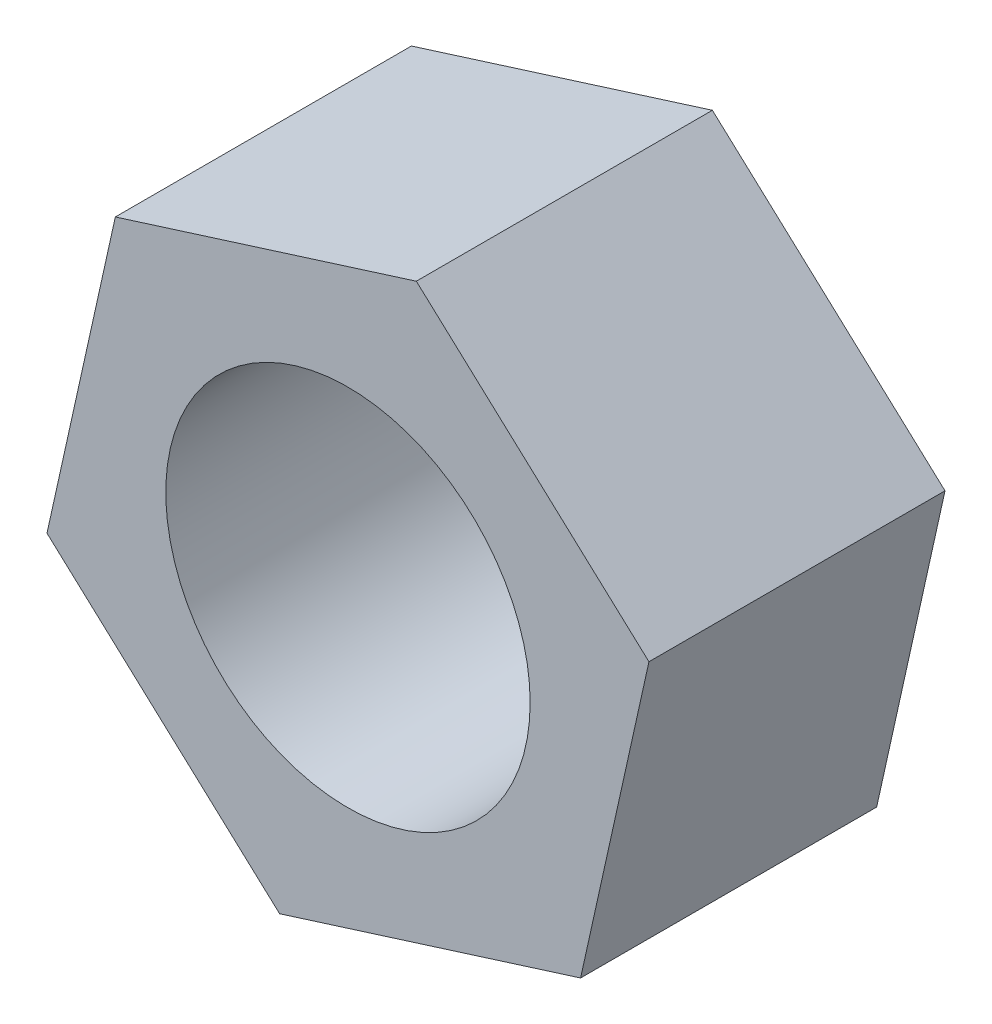
SolidWorks part; units mm, degrees
ref_plane "正面" through (0, 0, 0) normal (0, 0, 1) x (1, 0, 0)
ref_plane "平面" through (0, 0, 0) normal (0, 1, 0) x (1, 0, 0)
ref_plane "右側面" through (0, 0, 0) normal (1, 0, 0) x (0, 0, -1)
sketch "ｽｹｯﾁ1" plane through (0, 0, 0) normal (0, 0, 1) x (1, 0, 0)
  line L1 (10.2143, -9.3631) -> (13.2158, 4.1643)
  line L2 (13.2158, 4.1643) -> (3.0015, 13.5274)
  line L3 (3.0015, 13.5274) -> (-10.2143, 9.3631)
  line L4 (-10.2143, 9.3631) -> (-13.2158, -4.1643)
  line L5 (-13.2158, -4.1643) -> (-3.0015, -13.5274)
  line L6 (-3.0015, -13.5274) -> (10.2143, -9.3631)
  circle A0 centre (0, 0) radius 12 construction
  dimension "D1" = 24
extrude "ﾎﾞｽ - 押し出し1" add sketch "ｽｹｯﾁ1" along normal blind 13
sketch "ｽｹｯﾁ2" plane through (0, 0, 13) normal (0, 0, 1) x (1, 0, 0)
  circle A0 centre (0, 0) radius 8
  dimension "D1" = 16
extrude "ｶｯﾄ - 押し出し1" cut sketch "ｽｹｯﾁ2" against normal through all
